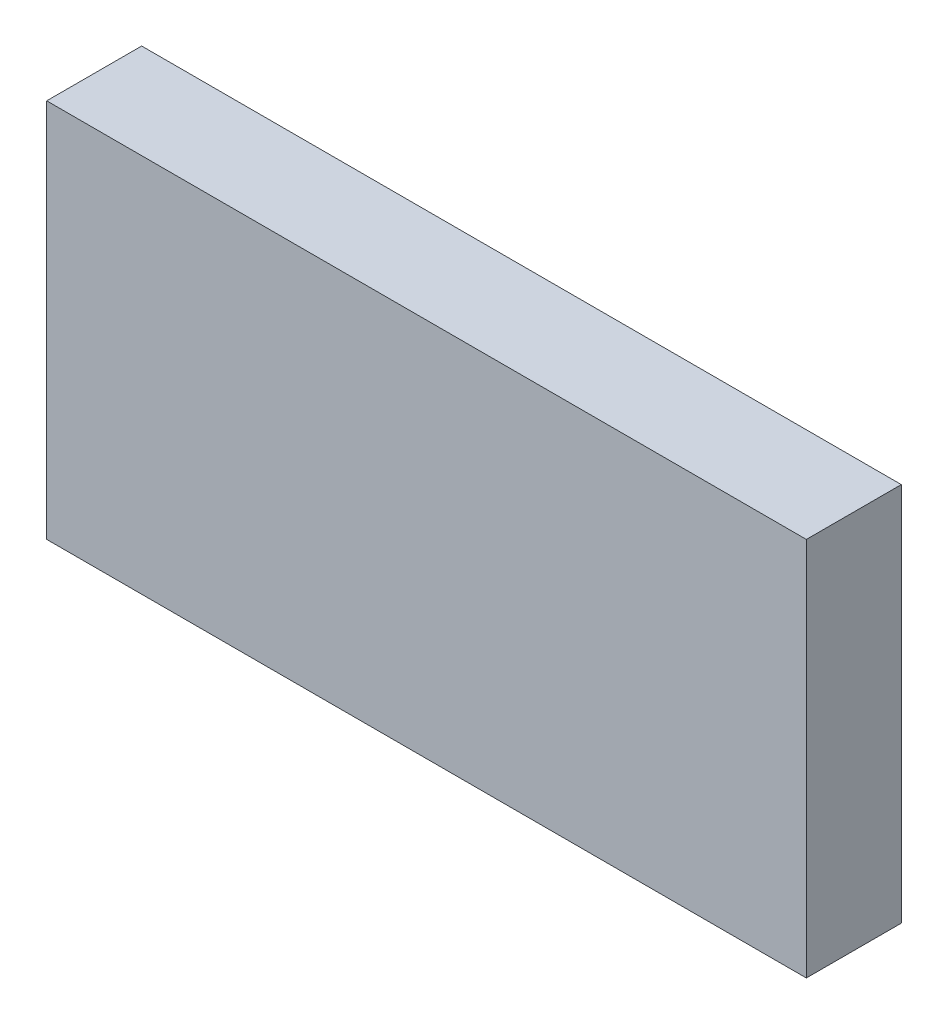
SolidWorks part; units mm, degrees
ref_plane "Front Plane" through (0, 0, 0) normal (0, 0, 1) x (1, 0, 0)
ref_plane "Top Plane" through (0, 0, 0) normal (0, 1, 0) x (1, 0, 0)
ref_plane "Right Plane" through (0, 0, 0) normal (1, 0, 0) x (0, 0, -1)
sketch "Sketch1" plane through (0, 0, 0) normal (0, 0, 1) x (1, 0, 0)
  line L1 (50.5859, -184) -> (74.5859, -184)
  line L2 (50.5859, -184) -> (50.5859, -196)
  line L3 (50.5859, -196) -> (74.5859, -196)
  line L4 (74.5859, -184) -> (74.5859, -196)
extrude "Boss-Extrude1" add sketch "Sketch1" along normal blind 3
